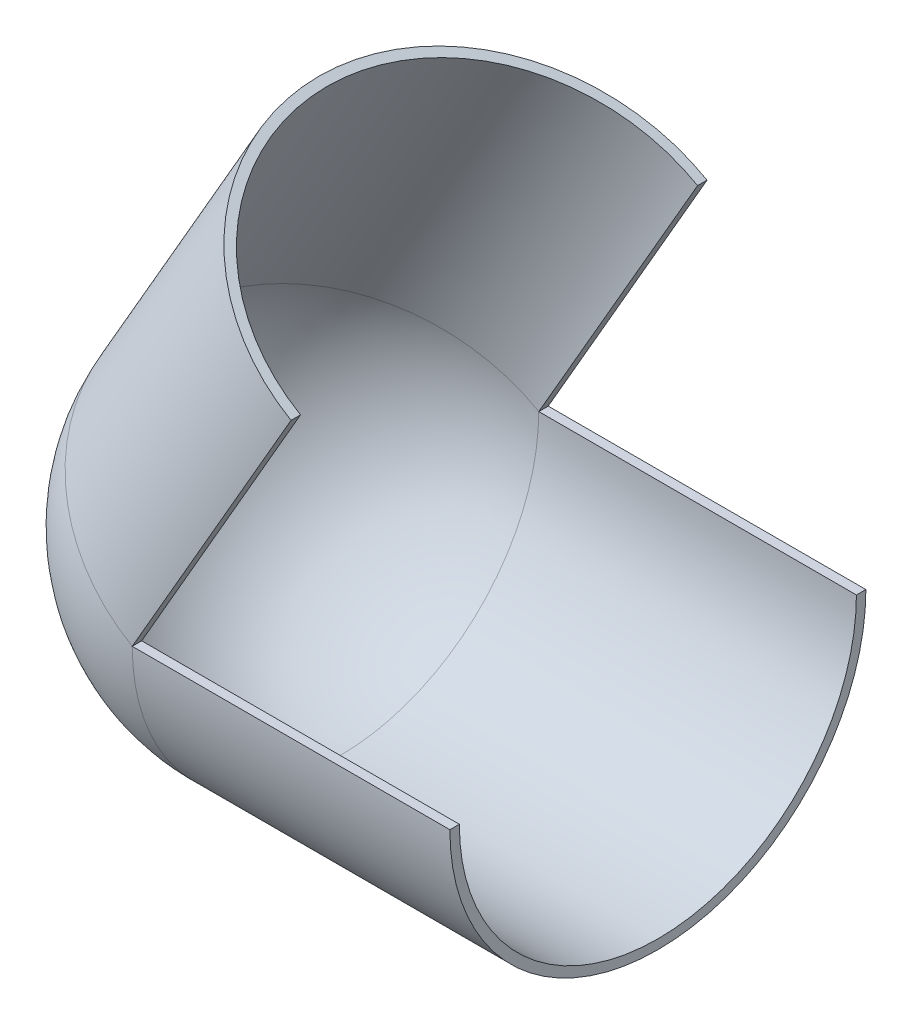
SolidWorks part; units mm, degrees
ref_plane "Front Plane" through (0, 0, 0) normal (0, 0, 1) x (1, 0, 0)
ref_plane "Top Plane" through (0, 0, 0) normal (0, 1, 0) x (1, 0, 0)
ref_plane "Right Plane" through (0, 0, 0) normal (1, 0, 0) x (0, 0, -1)
sketch "Sketch7" plane through (0, 0, 0) normal (1, 0, 0) x (0, 0, -1)
  line L0 (-133.0541, 0) -> (-127, 0)
  line L1 (127, 0) -> (133.0541, 0)
  line L2 (-127, 0) -> (127, 0) construction
  arc A0 (127, 0) -> (-127, 0) centre (0, 0) cw
  arc A1 (133.0541, 0) -> (-133.0541, 0) centre (0, 0) cw
  dimension "D1" = 127
revolve "Revolve4" add sketch "Sketch7" angle 120 about L2
sketch "Sketch8" plane through (0, 0, 0) normal (1, 0, 0) x (0, 0, -1)
  line L2 (-127, 0) -> (-133.0541, 0)
  line L3 (133.0541, 0) -> (127, 0)
  line L4 (-127, 0) -> (-133.0541, 0)
  line L5 (133.0541, 0) -> (127, 0)
  arc A2 (-127, 0) -> (127, 0) centre (0, 0) ccw
  arc A3 (-133.0541, 0) -> (133.0541, 0) centre (0, 0) ccw
  arc A4 (-127, 0) -> (127, 0) centre (0, 0) ccw
  arc A5 (-133.0541, 0) -> (133.0541, 0) centre (0, 0) ccw
  dimension "D1" = 0
extrude "Boss-Extrude3" add sketch "Sketch8" along normal blind 203.2
sketch "Sketch9" plane through (0, 0, 0) normal (0.5, 0.866, 0) x (0.866, -0.5, 0)
  line L2 (0, 127) -> (0, 133.0541)
  line L3 (0, -133.0541) -> (0, -127)
  line L4 (0, 127) -> (0, 133.0541)
  line L5 (0, -133.0541) -> (0, -127)
  arc A2 (0, 127) -> (0, -127) centre (0, 0) ccw
  arc A3 (0, 133.0541) -> (0, -133.0541) centre (0, 0) ccw
  arc A4 (0, 127) -> (0, -127) centre (0, 0) ccw
  arc A5 (0, 133.0541) -> (0, -133.0541) centre (0, 0) ccw
  dimension "D1" = 0
extrude "Boss-Extrude4" add sketch "Sketch9" along normal blind 203.2
